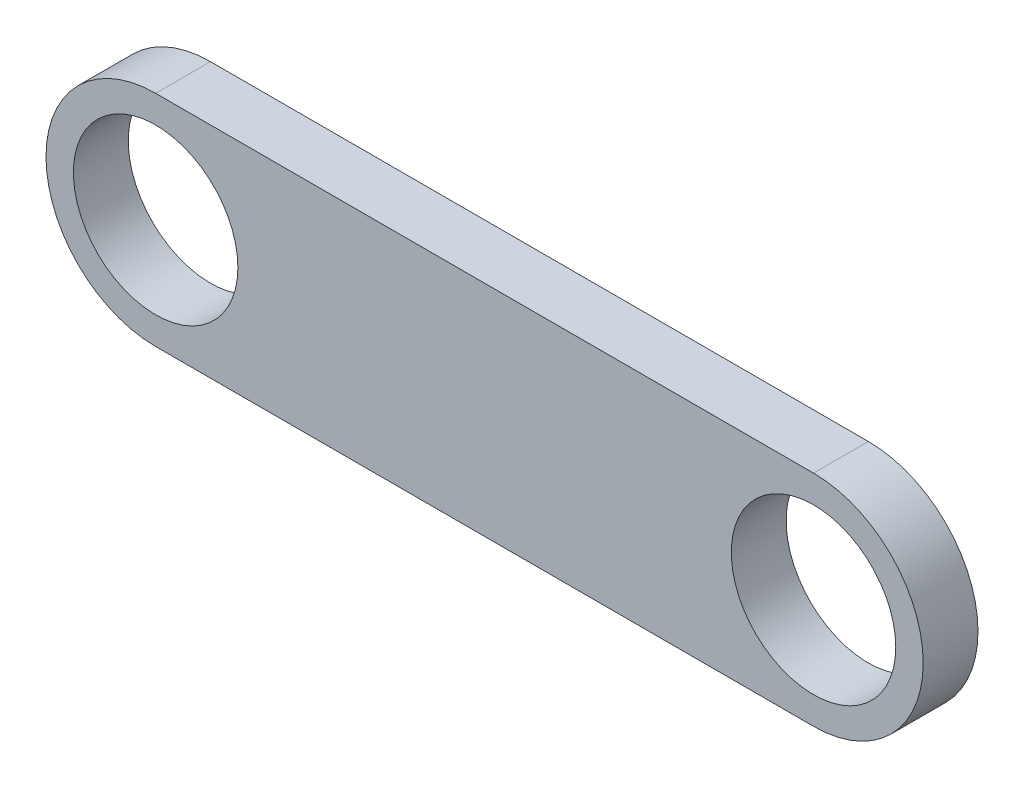
SolidWorks part; units mm, degrees
ref_plane "Спереди" through (0, 0, 0) normal (0, 0, 1) x (1, 0, 0)
ref_plane "Сверху" through (0, 0, 0) normal (0, 1, 0) x (1, 0, 0)
ref_plane "Справа" through (0, 0, 0) normal (1, 0, 0) x (0, 0, -1)
other "Configuration Table"
sketch "Эскиз1" plane through (0, 0, 0) normal (0, 0, 1) x (1, 0, 0)
  line L0 (0, 0) -> (120, 0) construction
  line L1 (0, 20) -> (120, 20)
  line L2 (0, -20) -> (120, -20)
  arc A0 (0, 20) -> (0, -20) centre (0, 0) ccw
  arc A1 (120, -20) -> (120, 20) centre (120, 0) ccw
  circle A2 centre (0, 0) radius 15
  circle A3 centre (120, 0) radius 15
  point P3 (60, 0)
  dimension "D3" = 30
  dimension "D4" = 30
  dimension "D1" = 120
  dimension "D2" = 40
extrude "Бобышка-Вытянуть1" add sketch "Эскиз1" along normal blind 10
